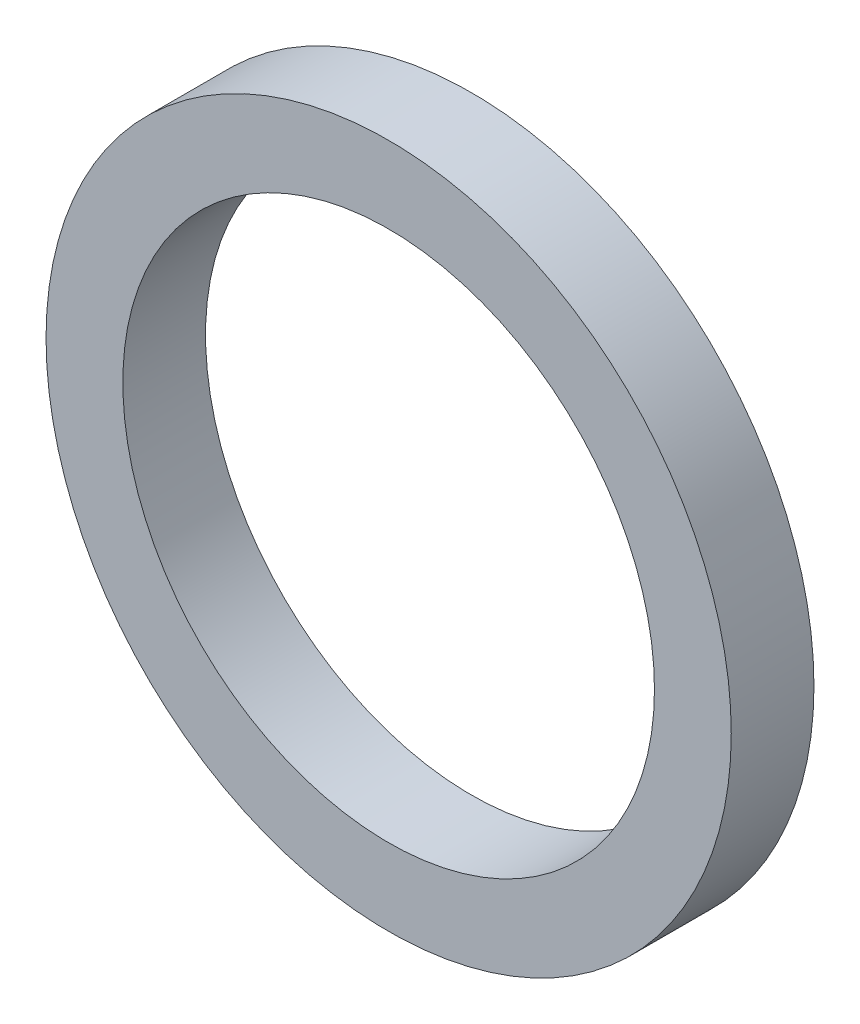
SolidWorks part; units mm, degrees
material "304不锈钢"
ref_plane "前视基准面" through (0, 0, 0) normal (0, 0, 1) x (1, 0, 0)
ref_plane "上视基准面" through (0, 0, 0) normal (0, 1, 0) x (1, 0, 0)
ref_plane "右视基准面" through (0, 0, 0) normal (1, 0, 0) x (0, 0, -1)
sketch "草图1" plane through (0, 0, 0) normal (0, 0, 1) x (1, 0, 0)
  circle A0 centre (0, 0) radius 29
  circle A1 centre (0, 0) radius 22.5
  dimension "D1" = 58
  dimension "D2" = 45
extrude "凸台-拉伸1" add sketch "草图1" along normal blind 7
